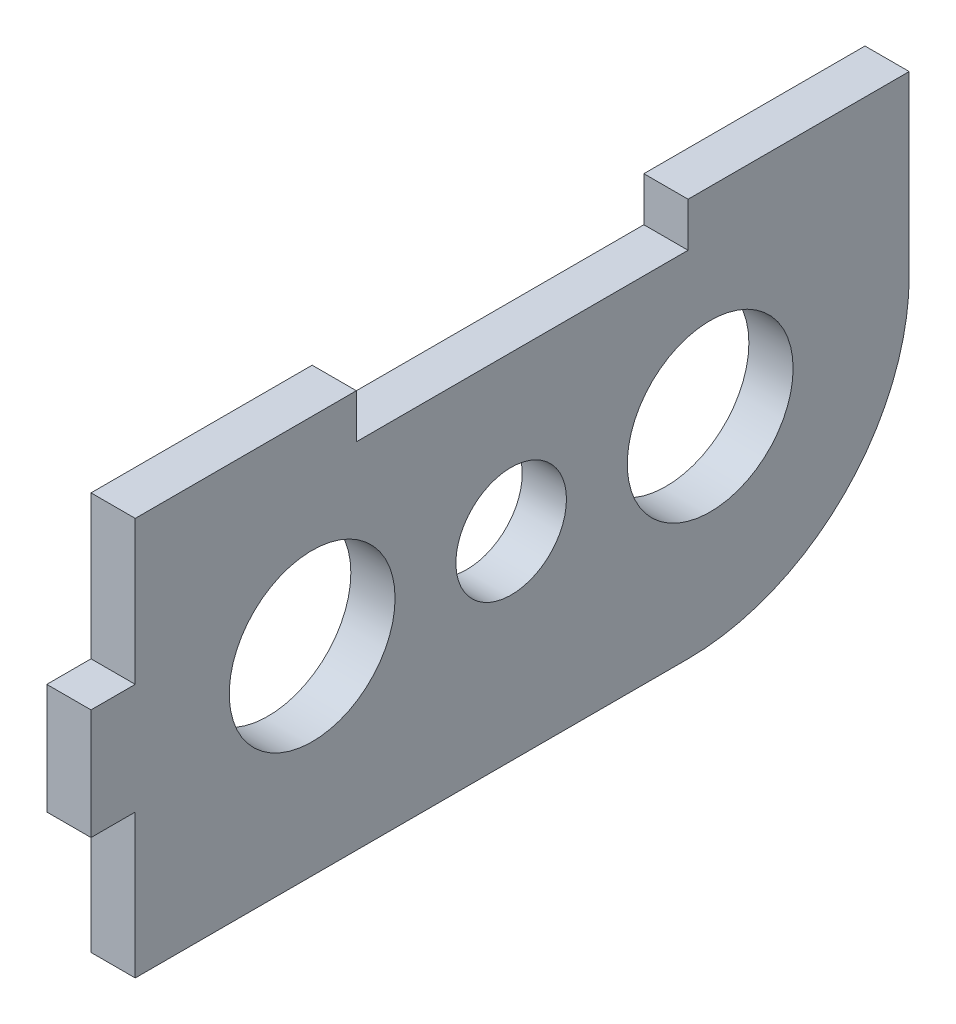
SolidWorks part; units mm, degrees
ref_plane "Front" through (0, 0, 0) normal (0, 0, 1) x (1, 0, 0)
ref_plane "Top" through (0, 0, 0) normal (0, 1, 0) x (1, 0, 0)
ref_plane "Right" through (0, 0, 0) normal (1, 0, 0) x (0, 0, -1)
sketch "Skizze1" plane through (0, 0, 0) normal (1, 0, 0) x (0, 0, -1)
  line L0 (0, 0) -> (74, 0) construction
  line L1 (0, -5) -> (0, 5)
  line L2 (0, 5) -> (4, 5)
  line L3 (4, 5) -> (4, 18)
  line L4 (4, 18) -> (74, 18)
  line L5 (74, 18) -> (74, -18)
  line L6 (4, -18) -> (74, -18)
  line L7 (4, -5) -> (4, -18)
  line L8 (0, -5) -> (4, -5)
  dimension "D1" = 4
  dimension "D2" = 10
  dimension "D3" = 36
  dimension "D4" = 70
extrude "Aufsatz-Linear austragen1" add sketch "Skizze1" along normal blind 4
sketch "Skizze2" [suppressed] plane through (4, 0, 0) normal (1, 0, 0) x (0, 0, -1)
  line L0 (39, 18) -> (39, 0) construction
  line L1 (4, 18) -> (24, 18)
  line L2 (4, 18) -> (4, 14)
  line L3 (4, 14) -> (24, 14)
  line L4 (24, 18) -> (24, 14)
  line L5 (74, 18) -> (54, 18)
  line L6 (74, 18) -> (74, 14)
  line L7 (74, 14) -> (54, 14)
  line L8 (54, 18) -> (54, 14)
  line L9 (74, 18) -> (4, 18) construction
  line L10 (39, 0) -> (0, 0) construction
  line L11 (54, -18) -> (54, -14)
  line L12 (74, -14) -> (54, -14)
  line L13 (74, -18) -> (74, -14)
  line L14 (74, -18) -> (54, -18)
  line L15 (24, -18) -> (24, -14)
  line L16 (4, -14) -> (24, -14)
  line L17 (4, -18) -> (4, -14)
  line L18 (4, -18) -> (24, -18)
  dimension "D1" = 4
  dimension "D2" = 30
extrude "Schnitt-Linear austragen1" [suppressed] cut sketch "Skizze2" against normal through all
sketch "Skizze3" plane through (4, 0, 0) normal (1, 0, 0) x (0, 0, -1)
  line L0 (74, 18) -> (4, 18) construction
  line L1 (24, 18) -> (54, 18)
  line L2 (24, 18) -> (24, 14)
  line L3 (24, 14) -> (54, 14)
  line L4 (54, 18) -> (54, 14)
  line L5 (39, -18) -> (39, 14) construction
  line L6 (4, -18) -> (74, -18) construction
  dimension "D1" = 4
  dimension "D2" = 30
extrude "Schnitt-Linear austragen2" cut sketch "Skizze3" against normal through all
sketch "Skizze4" [suppressed] plane through (4, 0, 0) normal (1, 0, 0) x (0, 0, -1)
  line L0 (0, 0) -> (32, 0) construction
  line L1 (37, 10) -> (27, 10) construction
  line L2 (37, 10) -> (37, -10) construction
  line L3 (37, -10) -> (27, -10) construction
  line L4 (27, 10) -> (27, -10) construction
  line L5 (37, 10) -> (27, -10) construction
  line L6 (37, -10) -> (27, 10) construction
  line L7 (0, 5) -> (0, -5) construction
  circle A0 centre (37, 10) radius 1.55
  circle A1 centre (27, 10) radius 1.55
  circle A2 centre (27, -10) radius 1.55
  circle A3 centre (37, -10) radius 1.55
  point P0 (32, 0)
  dimension "D3" = 3.1
  dimension "D1" = 10
  dimension "D2" = 20
  dimension "D4" = 32
extrude "Schnitt-Linear austragen3" [suppressed] cut sketch "Skizze4" against normal blind 10
fillet "Verrundung1" radius 20 1 edges at (2, -18, -74)
sketch "Skizze5" plane through (4, 0, 0) normal (1, 0, 0) x (0, 0, -1)
  line L0 (20, 0) -> (38, 0) construction
  line L1 (38, 0) -> (56, 0) construction
  line L2 (0, 5) -> (0, -5) construction
  line L3 (0, 0) -> (20, 0) construction
  circle A0 centre (20, 0) radius 7.5
  circle A1 centre (56, 0) radius 7.5
  circle A2 centre (38, 0) radius 5
  dimension "D1" = 15
  dimension "D2" = 10
  dimension "D3" = 18
  dimension "D4" = 20
extrude "Schnitt-Linear austragen4" cut sketch "Skizze5" against normal through all
sketch "Skizze6" [suppressed] plane through (4, 0, 0) normal (1, 0, 0) x (0, 0, -1)
  line L0 (20, 0) -> (56, 0) construction
  line L1 (20, 4) -> (56, 4)
  line L2 (20, -4) -> (56, -4)
  line L3 (4, 14) -> (4, 5) construction
  arc A0 (20, 4) -> (20, -4) centre (20, 0) ccw
  arc A1 (56, -4) -> (56, 4) centre (56, 0) ccw
  point P3 (38, 0)
  dimension "D1" = 4
  dimension "D2" = 36
  dimension "D3" = 16
extrude "Schnitt-Linear austragen5" [suppressed] cut sketch "Skizze6" against normal blind 10
